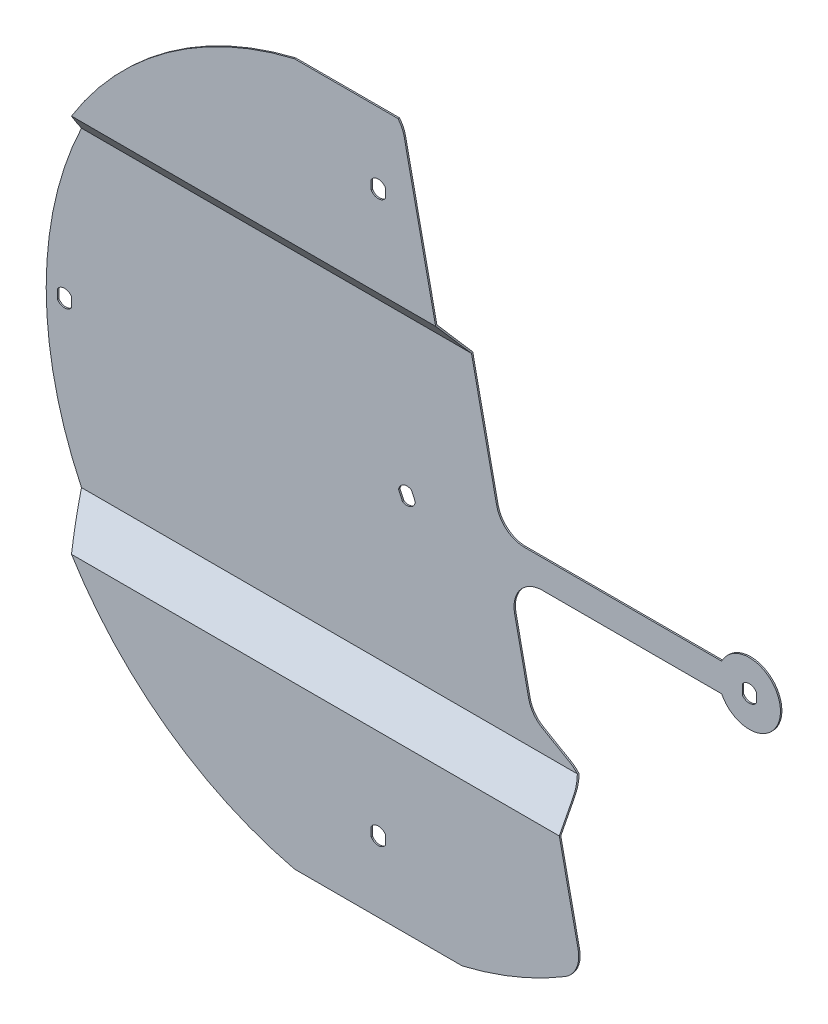
SolidWorks part; units mm, degrees
ref_plane "Alzado" through (0, 0, 0) normal (0, 0, 1) x (1, 0, 0)
ref_plane "Planta" through (0, 0, 0) normal (0, 1, 0) x (1, 0, 0)
ref_plane "Vista lateral" through (0, 0, 0) normal (1, 0, 0) x (0, 0, -1)
sketch "Croquis1" plane through (0, 0, 0) normal (1, 0, 0) x (0, 0, -1)
  line L0 (-36.5, -110) -> (-36.5, 110)
  line L1 (-36.5, 110) -> (-56.7478, 134.1304)
  line L2 (0, 0) -> (-82.8072, 0) construction
  line L3 (-56.7478, 134.1304) -> (-56.7478, 248)
  line L4 (-36.5, -110) -> (-56.7478, -134.1304)
  line L5 (-56.7478, -134.1304) -> (-56.7478, -248)
  line L6 (-55.7478, -134.4944) -> (-55.7478, -248)
  line L7 (-35.5, -110.364) -> (-55.7478, -134.4944)
  line L8 (-35.5, -110.364) -> (-35.5, 110.364)
  line L9 (-35.5, 110.364) -> (-55.7478, 134.4944)
  line L10 (-55.7478, 134.4944) -> (-55.7478, 248)
  line L11 (-56.7478, 248) -> (-55.7478, 248)
  line L12 (-56.7478, -248) -> (-55.7478, -248)
  point P9 (-36.5, 0)
  dimension "D1" = 36.5
  dimension "D2" = 50
  dimension "D3" = 31.5
  dimension "D4" = 110
  dimension "D5" = 496
  dimension "D6" = 1
extrude "Saliente-Extruir1" add sketch "Croquis1" along normal mid plane 542
sketch "Croquis2" plane through (0, 0, 0) normal (0, 0, 1) x (1, 0, 0)
  line L0 (344.6601, 0) -> (-344.6601, 0) construction
  line L1 (0, 276.4569) -> (0, -276.4569) construction
  line L2 (18.2641, 239.1381) -> (63.4097, 25.8583)
  line L3 (95.6184, -94.2882) -> (115.1117, -105.5426)
  line L4 (124.6782, -118.7215) -> (141.2293, -196.9134)
  line L5 (222.4041, 10) -> (82.9762, 10)
  line L6 (95.6766, -10) -> (222.4041, -10)
  line L7 (271, -110) -> (-271, -110) construction
  line L8 (76.1102, -34.1417) -> (86.052, -81.1094)
  line L34 (-384.7178, 325.8306) -> (384.7178, 325.8306)
  line L35 (-384.7178, 325.8306) -> (-384.7178, -325.8306)
  line L36 (-384.7178, -325.8306) -> (384.7178, -325.8306)
  line L37 (384.7178, 325.8306) -> (384.7178, -325.8306)
  line L38 (-384.7178, 325.8306) -> (384.7178, -325.8306) construction
  line L39 (-384.7178, -325.8306) -> (384.7178, 325.8306) construction
  arc A1 (222.4041, -10) -> (222.4041, 10) centre (242, 0) ccw
  arc A2 (-1.4132, 254.9961) -> (132.0172, -218.1662) centre (0, 0) ccw
  arc A3 (132.0172, -218.1662) -> (141.2293, -196.9134) centre (121.6629, -201.0551) ccw
  arc A4 (124.6782, -118.7215) -> (115.1117, -105.5426) centre (105.1117, -122.8632) ccw
  arc A5 (95.6184, -94.2882) -> (86.052, -81.1094) centre (105.6184, -76.9677) cw
  arc A6 (76.1102, -34.1417) -> (95.6766, -10) centre (95.6766, -30) cw
  arc A7 (82.9762, 10) -> (63.4097, 25.8583) centre (82.9762, 30) cw
  arc A8 (18.2641, 239.1381) -> (-1.4132, 254.9961) centre (-1.3024, 234.9964) ccw
  point P6 (0, 0)
  point P9 (0, 0)
  point P23 (122.8321, -110)
  point P28 (87.8981, -89.8308)
  point P31 (71, -10)
  point P36 (15, 254.5584)
  dimension "D1" = 255
  dimension "D3" = 44
  dimension "D9" = 20
  dimension "D2" = 242
  dimension "D4" = 15
  dimension "D5" = 20
  dimension "D6" = 71
  dimension "D7" = 30
  dimension "D8" = 30
extrude "Cortar-Extruir6" cut sketch "Croquis2" against normal through all both and the other way through all contours L37 L34 L35 L36 A8 L2 A7 L5 A1 L6 A6 L8 A5 L3 A4 L4 A3 A2
sketch "Croquis4" plane through (0, 0, 0) normal (0, 0, 1) x (1, 0, 0)
  line L0 (-326.6263, 0) -> (326.6263, 0) construction
  line L1 (0, 278.5393) -> (0, -278.5393) construction
  line L2 (-5, -194.6834) -> (5, -201.3166) construction
  line L3 (-5, 201.3166) -> (5, 201.3166) construction
  line L4 (-5, 201.3166) -> (-5, 194.6834)
  line L5 (-5, 194.6834) -> (5, 194.6834) construction
  line L6 (5, 201.3166) -> (5, 194.6834)
  line L7 (-5, 201.3166) -> (5, 194.6834) construction
  line L8 (-5, 194.6834) -> (5, 201.3166) construction
  line L9 (-5, -201.3166) -> (5, -194.6834) construction
  line L10 (-5, -194.6834) -> (5, -194.6834) construction
  line L11 (-5, -201.3166) -> (5, -201.3166) construction
  line L12 (5, -201.3166) -> (5, -194.6834)
  line L13 (-5, -201.3166) -> (-5, -194.6834)
  line L14 (247, -3.3166) -> (237, 3.3166) construction
  line L15 (-247, 3.3166) -> (-237, 3.3166) construction
  line L16 (-247, 3.3166) -> (-247, -3.3166)
  line L17 (-247, -3.3166) -> (-237, -3.3166) construction
  line L18 (-237, 3.3166) -> (-237, -3.3166)
  line L19 (-247, 3.3166) -> (-237, -3.3166) construction
  line L20 (-247, -3.3166) -> (-237, 3.3166) construction
  line L21 (247, 3.3166) -> (237, -3.3166) construction
  line L22 (247, -3.3166) -> (237, -3.3166) construction
  line L23 (247, 3.3166) -> (237, 3.3166) construction
  line L24 (237, 3.3166) -> (237, -3.3166)
  line L25 (247, 3.3166) -> (247, -3.3166)
  line L26 (-5.9332, 0.8928) -> (3.1299, 5.119) construction
  line L27 (-5.9332, 0.8928) -> (-3.1299, -5.119)
  line L28 (3.1299, 5.119) -> (5.9332, -0.8928)
  line L29 (-3.1299, -5.119) -> (5.9332, -0.8928) construction
  line L30 (0, 0) -> (-1.4017, 3.0059) construction
  arc A0 (-5, 194.6834) -> (5, 194.6834) centre (0, 198) ccw
  arc A1 (-3.1299, -5.119) -> (5.9332, -0.8928) centre (0, 0) ccw
  arc A2 (-247, -3.3166) -> (-237, -3.3166) centre (-242, 0) ccw
  arc A4 (5, 201.3166) -> (-5, 201.3166) centre (0, 198) ccw
  arc A5 (5, -201.3166) -> (-5, -201.3166) centre (0, -198) cw
  arc A6 (-5, -194.6834) -> (5, -194.6834) centre (0, -198) cw
  arc A7 (-237, 3.3166) -> (-247, 3.3166) centre (-242, 0) ccw
  arc A8 (237, 3.3166) -> (247, 3.3166) centre (242, 0) cw
  arc A9 (247, -3.3166) -> (237, -3.3166) centre (242, 0) cw
  arc A10 (3.1299, 5.119) -> (-5.9332, 0.8928) centre (0, 0) ccw
  point P4 (0, 0)
  point P8 (0, 0)
  dimension "D3" = 12
  dimension "D4" = 10
  dimension "D5" = 12
  dimension "D6" = 12
  dimension "D1" = 198
  dimension "D2" = 242
  dimension "D7" = 10
  dimension "D8" = 10
  dimension "D9" = 25
extrude "Cortar-Extruir9" cut sketch "Croquis4" against normal through all both and the other way through all
